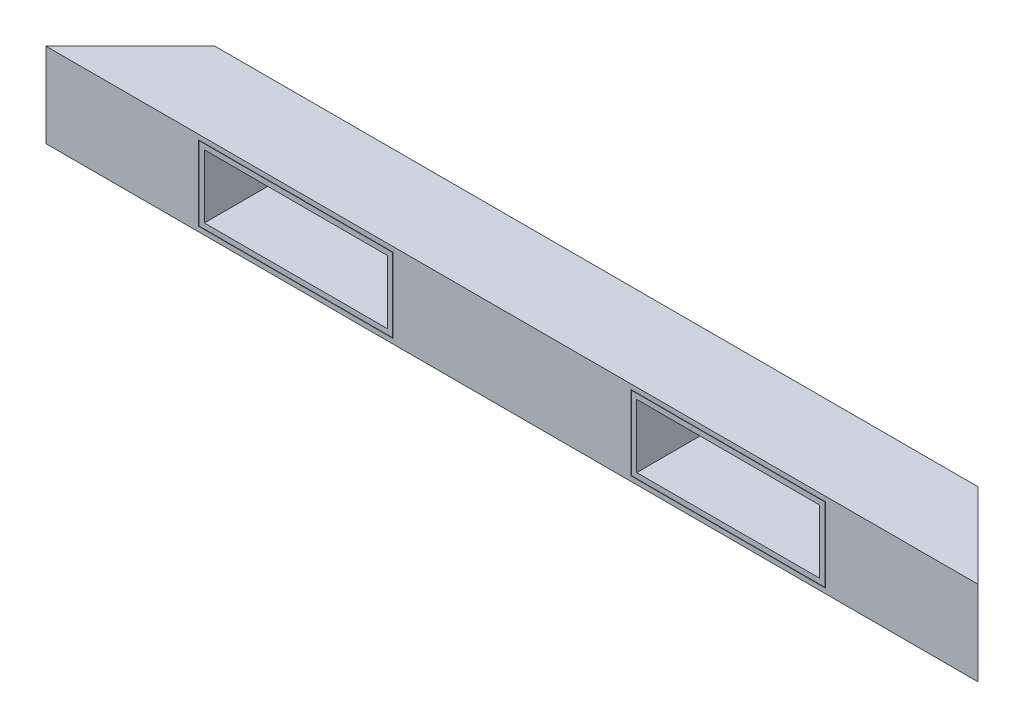
SolidWorks part; units mm, degrees
ref_plane "Alzado" through (0, 0, 0) normal (0, 0, 1) x (1, 0, 0)
ref_plane "Planta" through (0, 0, 0) normal (0, 1, 0) x (1, 0, 0)
ref_plane "Vista lateral" through (0, 0, 0) normal (1, 0, 0) x (0, 0, -1)
sketch "Croquis1" plane through (0, 0, 0) normal (0, 0, 1) x (1, 0, 0)
  line L1 (0, 0) -> (1120.95, 0)
  line L2 (0, 0) -> (0, 101.6)
  line L3 (0, 101.6) -> (1120.95, 101.6)
  line L4 (1120.95, 0) -> (1120.95, 101.6)
  dimension "D1" = 101.6
  dimension "D2" = 1120.95
extrude "Saliente-Extruir1" add sketch "Croquis1" against normal blind 101.6
sketch "Croquis3" plane through (1120.95, 0, 0) normal (1, 0, 0) x (0, 0, -1)
  line L0 (50.8, 101.6) -> (50.8, 50.8) construction
  line L1 (101.6, 101.6) -> (0, 101.6) construction
  line L2 (50.8, 50.8) -> (0, 50.8) construction
  line L3 (0, 0) -> (0, 101.6) construction
  line L4 (101.6, 0) -> (101.6, 101.6) construction
  line L5 (95.25, 6.35) -> (6.35, 6.35)
  line L6 (95.25, 6.35) -> (95.25, 95.25)
  line L7 (95.25, 95.25) -> (6.35, 95.25)
  line L8 (6.35, 6.35) -> (6.35, 95.25)
  line L9 (95.25, 6.35) -> (6.35, 95.25) construction
  line L10 (95.25, 95.25) -> (6.35, 6.35) construction
  dimension "D1" = 6.35
  dimension "D2" = 6.35
  dimension "D3" = 6.35
extrude "Cortar-Extruir1" cut sketch "Croquis3" against normal up to surface (1120.95 mm away) up to face at (0, 50.8, -50.8)
sketch "Croquis4" plane through (0, 101.6, 0) normal (0, 1, 0) x (1, 0, 0)
  line L0 (0, 101.6) -> (101.6, 101.6)
  line L2 (1120.95, 101.6) -> (0, 101.6) construction
  line L3 (0, 0) -> (101.6, 101.6)
  line L4 (0, 0) -> (0, 101.6)
  line L5 (0, 101.6) -> (-0.5161, 101.7765)
  line L6 (560.475, 0) -> (560.475, 101.6) construction
  line L7 (1120.95, 0) -> (0, 0) construction
  line L8 (1120.95, 101.6) -> (1121.4661, 101.7765)
  line L9 (1120.95, 0) -> (1120.95, 101.6)
  line L10 (1120.95, 0) -> (1019.35, 101.6)
  line L11 (1120.95, 101.6) -> (1019.35, 101.6)
  line M4 (1120.95, 0) -> (1120.95, 101.6)
  line M5 (1120.95, 101.6) -> (0, 101.6)
  line M6 (0, 101.6) -> (0, 0)
  dimension "D1" = 101.6
extrude "Cortar-Extruir2" cut sketch "Croquis4" against normal blind 101.6 contours L10 M4 M5 | L3 M6 M5
sketch "Croquis5" plane through (0, 0, 0) normal (0, 0, 1) x (1, 0, 0)
  line L0 (0, 50.8) -> (1120.95, 50.8) construction
  line L1 (0, 101.6) -> (0, 0) construction
  line L2 (1120.95, 0) -> (1120.95, 101.6) construction
  line L3 (560.475, 0) -> (560.475, 101.6) construction
  line L4 (410.475, 12.7) -> (190.475, 12.7)
  line L5 (410.475, 12.7) -> (410.475, 88.9)
  line L6 (410.475, 88.9) -> (190.475, 88.9)
  line L7 (190.475, 12.7) -> (190.475, 88.9)
  line L8 (410.475, 12.7) -> (190.475, 88.9) construction
  line L9 (410.475, 88.9) -> (190.475, 12.7) construction
  line L10 (0, 0) -> (1120.95, 0) construction
  line L11 (1120.95, 101.6) -> (0, 101.6) construction
  line L12 (710.475, 88.9) -> (930.475, 12.7) construction
  line L13 (710.475, 12.7) -> (930.475, 88.9) construction
  line L14 (930.475, 12.7) -> (930.475, 88.9)
  line L15 (710.475, 88.9) -> (930.475, 88.9)
  line L16 (710.475, 12.7) -> (710.475, 88.9)
  line L17 (710.475, 12.7) -> (930.475, 12.7)
  point P6 (300.475, 50.8)
  point P21 (820.475, 50.8)
  dimension "D1" = 220
  dimension "D2" = 190.475
  dimension "D3" = 76.2
extrude "Cortar-Extruir3" cut sketch "Croquis5" against normal up to surface (101.6 mm away) up to face at (560.475, 50.8, -101.6)
sketch "Croquis6" plane through (0, 0, 0) normal (0, 0, 1) x (1, 0, 0)
  line L0 (560.475, 0) -> (560.475, 101.6) construction
  line L1 (190.475, 88.9) -> (410.475, 88.9)
  line L2 (190.475, 88.9) -> (190.475, 12.7)
  line L3 (190.475, 12.7) -> (410.475, 12.7)
  line L4 (410.475, 88.9) -> (410.475, 12.7)
  line L5 (416.825, 6.35) -> (184.125, 6.35)
  line L6 (416.825, 6.35) -> (416.825, 95.25)
  line L7 (416.825, 95.25) -> (184.125, 95.25)
  line L8 (184.125, 6.35) -> (184.125, 95.25)
  line L9 (416.825, 6.35) -> (184.125, 95.25) construction
  line L10 (416.825, 95.25) -> (184.125, 6.35) construction
  line L11 (0, 0) -> (1120.95, 0) construction
  line L12 (1120.95, 101.6) -> (0, 101.6) construction
  line L13 (704.125, 95.25) -> (936.825, 6.35) construction
  line L14 (704.125, 6.35) -> (936.825, 95.25) construction
  line L15 (936.825, 6.35) -> (936.825, 95.25)
  line L16 (704.125, 95.25) -> (936.825, 95.25)
  line L17 (704.125, 6.35) -> (704.125, 95.25)
  line L18 (704.125, 6.35) -> (936.825, 6.35)
  line L19 (710.475, 88.9) -> (710.475, 12.7)
  line L20 (930.475, 12.7) -> (710.475, 12.7)
  line L21 (930.475, 88.9) -> (930.475, 12.7)
  line L22 (930.475, 88.9) -> (710.475, 88.9)
  point P6 (300.475, 50.8)
  point P25 (820.475, 50.8)
  dimension "D1" = 6.35
  dimension "D2" = 6.35
  dimension "D3" = 6.35
  dimension "D4" = 6.35
extrude "Saliente-Extruir2" add sketch "Croquis6" against normal up to surface (101.6 mm away) up to face at (820.475, 50.8, -101.6)
sketch "Croquis7" plane through (0, 0, 0) normal (0, 0, 1) x (1, 0, 0)
  line L0 (300.475, 88.9) -> (300.475, 12.7) construction
  line L1 (410.475, 88.9) -> (190.475, 88.9) construction
  line L2 (190.475, 12.7) -> (410.475, 12.7) construction
  line L3 (190.475, 88.9) -> (190.475, 12.7) construction
  line L4 (416.825, 6.35) -> (184.125, 6.35)
  line L5 (416.825, 6.35) -> (416.825, 95.25)
  line L6 (416.825, 95.25) -> (184.125, 95.25)
  line L7 (184.125, 6.35) -> (184.125, 95.25)
  line L8 (416.825, 6.35) -> (184.125, 95.25) construction
  line L9 (416.825, 95.25) -> (184.125, 6.35) construction
  line L11 (560.475, 0) -> (560.475, 101.6) construction
  line L12 (0, 0) -> (1120.95, 0) construction
  line L13 (1120.95, 101.6) -> (0, 101.6) construction
  line L14 (820.475, 88.9) -> (820.475, 12.7) construction
  line L15 (930.475, 88.9) -> (710.475, 88.9) construction
  line L16 (710.475, 12.7) -> (930.475, 12.7) construction
  line L17 (930.475, 12.7) -> (930.475, 88.9) construction
  line L18 (936.825, 6.35) -> (704.125, 6.35)
  line L19 (936.825, 6.35) -> (936.825, 95.25)
  line L20 (936.825, 95.25) -> (704.125, 95.25)
  line L21 (704.125, 6.35) -> (704.125, 95.25)
  line L22 (936.825, 6.35) -> (704.125, 95.25) construction
  line L23 (936.825, 95.25) -> (704.125, 6.35) construction
  line L26 (417.325, 5.85) -> (183.625, 5.85)
  line L27 (417.325, 5.85) -> (417.325, 95.75)
  line L28 (417.325, 95.75) -> (183.625, 95.75)
  line L29 (183.625, 5.85) -> (183.625, 95.75)
  line L30 (417.325, 5.85) -> (183.625, 95.75) construction
  line L31 (417.325, 95.75) -> (183.625, 5.85) construction
  line L32 (937.325, 5.85) -> (703.625, 5.85)
  line L33 (937.325, 5.85) -> (937.325, 95.75)
  line L34 (937.325, 95.75) -> (703.625, 95.75)
  line L35 (703.625, 5.85) -> (703.625, 95.75)
  line L36 (937.325, 5.85) -> (703.625, 95.75) construction
  line L37 (937.325, 95.75) -> (703.625, 5.85) construction
  point P6 (300.475, 50.8)
  point P25 (820.475, 50.8)
  point P32 (820.475, 50.8)
  point P34 (300.475, 50.8)
  dimension "D1" = 6.35
  dimension "D2" = 6.35
  dimension "D3" = 6.35
  dimension "D4" = 6.35
  dimension "D5" = 6.35
  dimension "D6" = 0.5
  dimension "D7" = 0.5
  dimension "D8" = 0.5
  dimension "D9" = 0.5
extrude "Cortar-Extruir4" cut sketch "Croquis7" against normal up to surface (101.6 mm away) up to face at (560.475, 50.8, -101.6)
